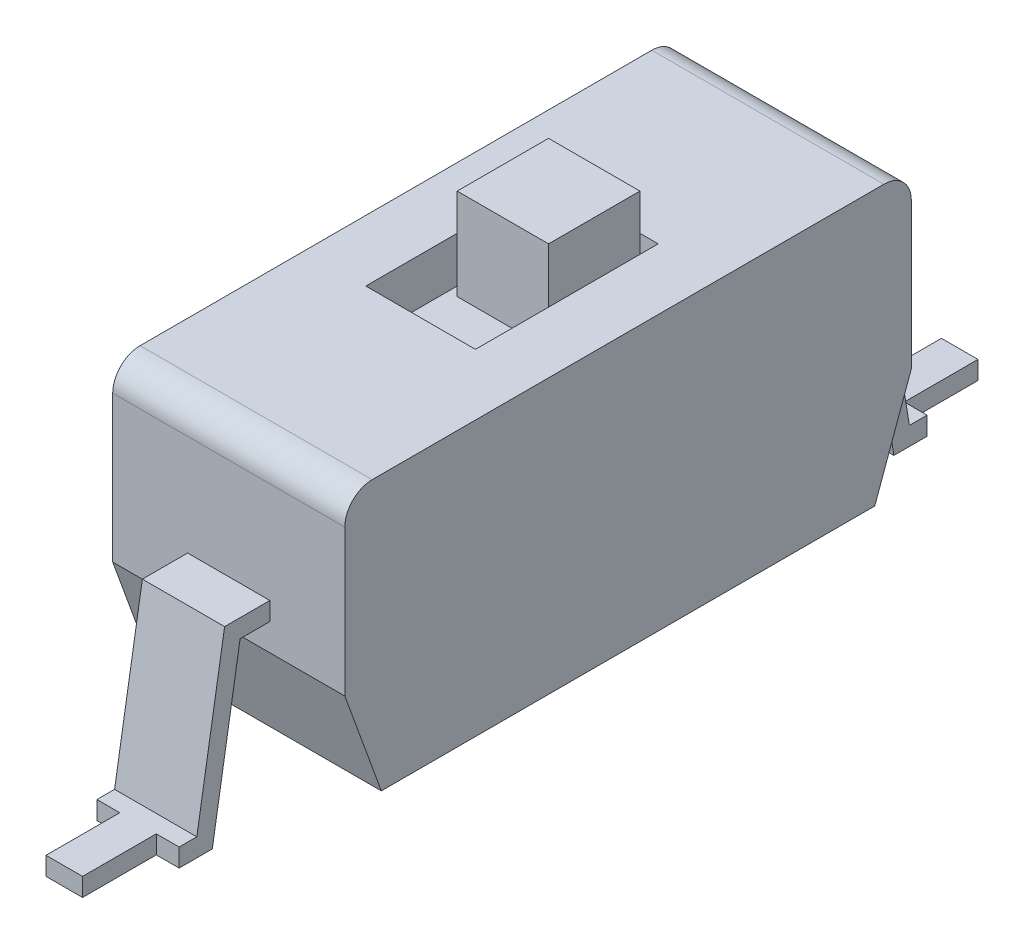
SolidWorks part; units mm, degrees
ref_plane "前视基准面" through (0, 0, 0) normal (0, 0, 1) x (1, 0, 0)
ref_plane "上视基准面" through (0, 0, 0) normal (0, 1, 0) x (1, 0, 0)
ref_plane "右视基准面" through (0, 0, 0) normal (1, 0, 0) x (0, 0, -1)
sketch "草图1" plane through (0, 0, 0) normal (0, 1, 0) x (1, 0, 0)
  line L0 (-25.8641, 0) -> (23.6912, 0) construction
  line L1 (-1.27, 3.1) -> (1.27, 3.1)
  line L2 (-1.27, 3.1) -> (-1.27, -3.1)
  line L3 (-1.27, -3.1) -> (1.27, -3.1)
  line L4 (1.27, 3.1) -> (1.27, -3.1)
  line L5 (0, 27.0034) -> (0, -30.5011) construction
  dimension "D1" = 2.54
  dimension "D2" = 6.2
extrude "拉伸1" add sketch "草图1" along normal blind 3
sketch "草图2" plane through (0, 3, 0) normal (0, 1, 0) x (1, 0, 0)
  line L0 (0, 4.1013) -> (0, -4.9096) construction
  line L1 (-0.6, 1) -> (0.6, 1)
  line L2 (-0.6, 1) -> (-0.6, -1)
  line L3 (-0.6, -1) -> (0.6, -1)
  line L4 (0.6, 1) -> (0.6, -1)
  line L5 (-2.6262, 0) -> (2.5723, 0) construction
  dimension "D1" = 2
  dimension "D2" = 1.2
extrude "切除-拉伸1" cut sketch "草图2" against normal blind 0.5
sketch "草图3" plane through (0, 2.5, 0) normal (0, 1, 0) x (1, 0, 0)
  line L0 (0, 1.6905) -> (0, -2.2591) construction
  line L1 (-0.5, 0.9) -> (0.5, 0.9)
  line L2 (-0.5, 0.9) -> (-0.5, -0.1)
  line L3 (-0.5, -0.1) -> (0.5, -0.1)
  line L4 (0.5, 0.9) -> (0.5, -0.1)
  line L5 (0.6, 1) -> (-0.6, 1) construction
  dimension "D1" = 1
  dimension "D2" = 1
  dimension "D3" = 0.1
extrude "凸台-拉伸1" add sketch "草图3" along normal blind 1
fillet "圆角1" radius 0.3 2 edges at (0, 3, -3.1) (0, 3, 3.1)
chamfer "倒角1" distance 0.4 angle 70 2 edges at (0, 0, -3.1) (0, 0, 3.1)
sketch "草图4" plane through (0, 0, 0) normal (1, 0, 0) x (0, 0, -1)
  line L0 (-2.9421, 1.5948) -> (-3.5953, 1.5948)
  line L1 (-3.5953, 1.5948) -> (-3.8995, -0.2454)
  line L2 (-3.8995, -0.2454) -> (-4.9, -0.2454)
  line L3 (-4.9, -0.2454) -> (-4.9, -0.4454)
  line L4 (-4.9, -0.4454) -> (-3.7298, -0.4454)
  line L5 (-3.7298, -0.4454) -> (-3.4257, 1.3948)
  line L6 (-3.4257, 1.3948) -> (-2.9421, 1.3948)
  line L7 (-2.9421, 1.3948) -> (-2.9421, 1.5948)
  line L8 (0, 5.0891) -> (0, -2.8492) construction
  line L9 (2.9421, 1.3948) -> (2.9421, 1.5948)
  line L10 (3.4257, 1.3948) -> (2.9421, 1.3948)
  line L11 (3.7298, -0.4454) -> (3.4257, 1.3948)
  line L12 (4.9, -0.4454) -> (3.7298, -0.4454)
  line L13 (4.9, -0.2454) -> (4.9, -0.4454)
  line L14 (3.8995, -0.2454) -> (4.9, -0.2454)
  line L15 (3.5953, 1.5948) -> (3.8995, -0.2454)
  line L16 (2.9421, 1.5948) -> (3.5953, 1.5948)
  dimension "D1" = 0.2
  dimension "D2" = 0.2
  dimension "D3" = 0.2
  dimension "D4" = 9.8
extrude "凸台-拉伸2" add sketch "草图4" along normal blind 0.45 and the other way blind 0.45
sketch "草图5" plane through (0, -0.2454, 0) normal (0, 1, 0) x (1, 0, 0)
  line L0 (0, 7.7519) -> (0, -7.8837) construction
  line L1 (0.2, 4.9) -> (0.2, 4.0929)
  line L2 (-0.45, 4.9) -> (-0.2, 4.9)
  line L3 (-0.45, 4.9) -> (-0.45, 4.0929)
  line L4 (-0.45, 4.0929) -> (-0.2, 4.0929)
  line L5 (-0.2, 4.9) -> (-0.2, 4.0929)
  line L6 (0.45, 4.0929) -> (0.2, 4.0929)
  line L7 (0.45, 4.9) -> (0.45, 4.0929)
  line L8 (0.45, 4.9) -> (0.2, 4.9)
  line L9 (-2.05, 0) -> (2.6344, 0) construction
  line L10 (0.45, -4.9) -> (0.2, -4.9)
  line L11 (0.45, -4.9) -> (0.45, -4.0929)
  line L12 (0.45, -4.0929) -> (0.2, -4.0929)
  line L13 (-0.2, -4.9) -> (-0.2, -4.0929)
  line L14 (-0.45, -4.0929) -> (-0.2, -4.0929)
  line L15 (-0.45, -4.9) -> (-0.45, -4.0929)
  line L16 (-0.45, -4.9) -> (-0.2, -4.9)
  line L17 (0.2, -4.9) -> (0.2, -4.0929)
  dimension "D1" = 0.4
extrude "切除-拉伸2" cut sketch "草图5" against normal blind 0.45
